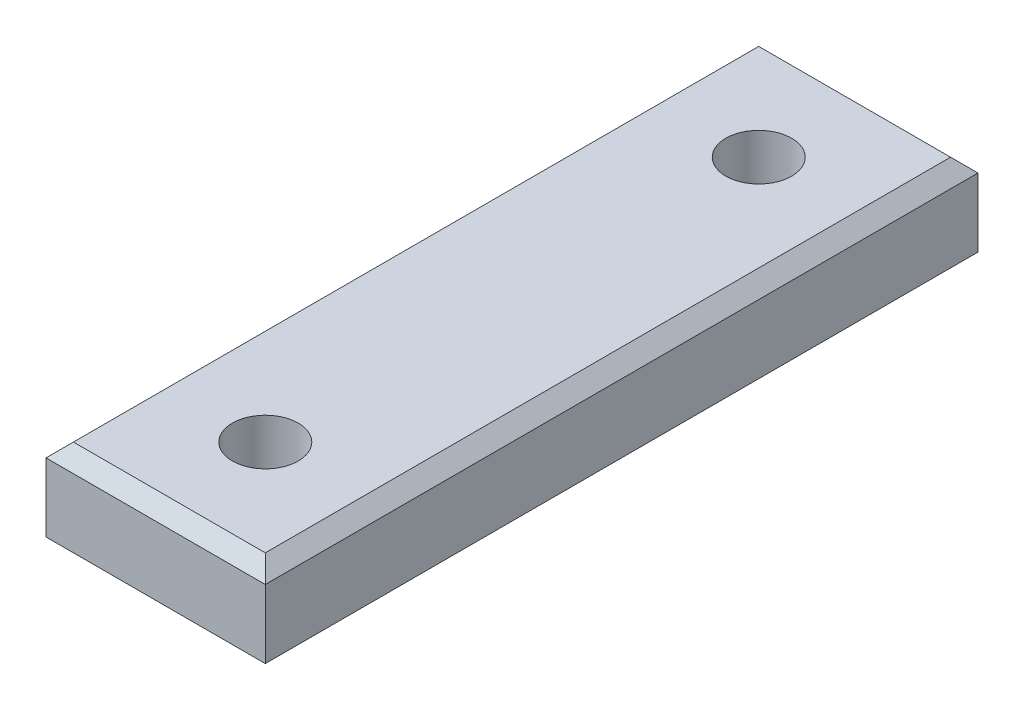
SolidWorks part; units mm, degrees
ref_plane "Front Plane" through (0, 0, 0) normal (0, 0, 1) x (1, 0, 0)
ref_plane "Top Plane" through (0, 0, 0) normal (0, 1, 0) x (1, 0, 0)
ref_plane "Right Plane" through (0, 0, 0) normal (1, 0, 0) x (0, 0, -1)
sketch "Sketch1" plane through (0, 0, 0) normal (0, 0, 1) x (1, 0, 0)
  line L1 (-4, 1.75) -> (4, 1.75)
  line L2 (-4, 1.75) -> (-4, -1.75)
  line L3 (-4, -1.75) -> (4, -1.75)
  line L4 (4, 1.75) -> (4, -1.75)
  line L5 (0, -1.75) -> (0, 1.75) construction
  line L6 (-4, 0) -> (4, 0) construction
  point P0 (0, 0)
  dimension "D1" = 3.5
  dimension "D2" = 8
extrude "Boss-Extrude1" add sketch "Sketch1" along normal mid plane 10
sketch "Sketch2" plane through (0, 0, -5) normal (0, 0, -1) x (-1, 0, 0)
  line L1 (-4, 1.75) -> (4, 1.75)
  line L2 (-4, 1.75) -> (-4, -1.75)
  line L3 (-4, -1.75) -> (4, -1.75)
  line L4 (4, 1.75) -> (4, -1.75)
  line L5 (0, -1.75) -> (0, 1.75) construction
  line L6 (-4, 0) -> (4, 0) construction
  point P0 (0, 0)
  dimension "D1" = 3.5
  dimension "D2" = 8
extrude "Boss-Extrude2" add sketch "Sketch2" along normal blind 8
mirror "Mirror1" about plane through (0, 0, 0) normal (0, 0, 1) of "Boss-Extrude2"
chamfer "Chamfer1" distance 0.5 angle 45 8 edges at (-4, 1.75, 0) (0, -1.75, 13) (0, 1.75, 13) (0, 1.75, -13) (4, 1.75, 0) (-4, -1.75, 0) (4, -1.75, 0) (0, -1.75, -13)
sketch "Sketch3" plane through (0, 1.75, 0) normal (0, 1, 0) x (1, 0, 0)
  line L0 (0, 13) -> (0, -13) construction
  line L1 (-4, 13) -> (4, 13) construction
  line L2 (4, -13) -> (-4, -13) construction
  circle A0 centre (0, -9) radius 1.2
  circle A1 centre (0, 9) radius 1.2
  dimension "D1" = 2.4
  dimension "D2" = 2.4
  dimension "D3" = 4
  dimension "D4" = 4
extrude "Cut-Extrude1" cut sketch "Sketch3" against normal through all both and the other way through all
